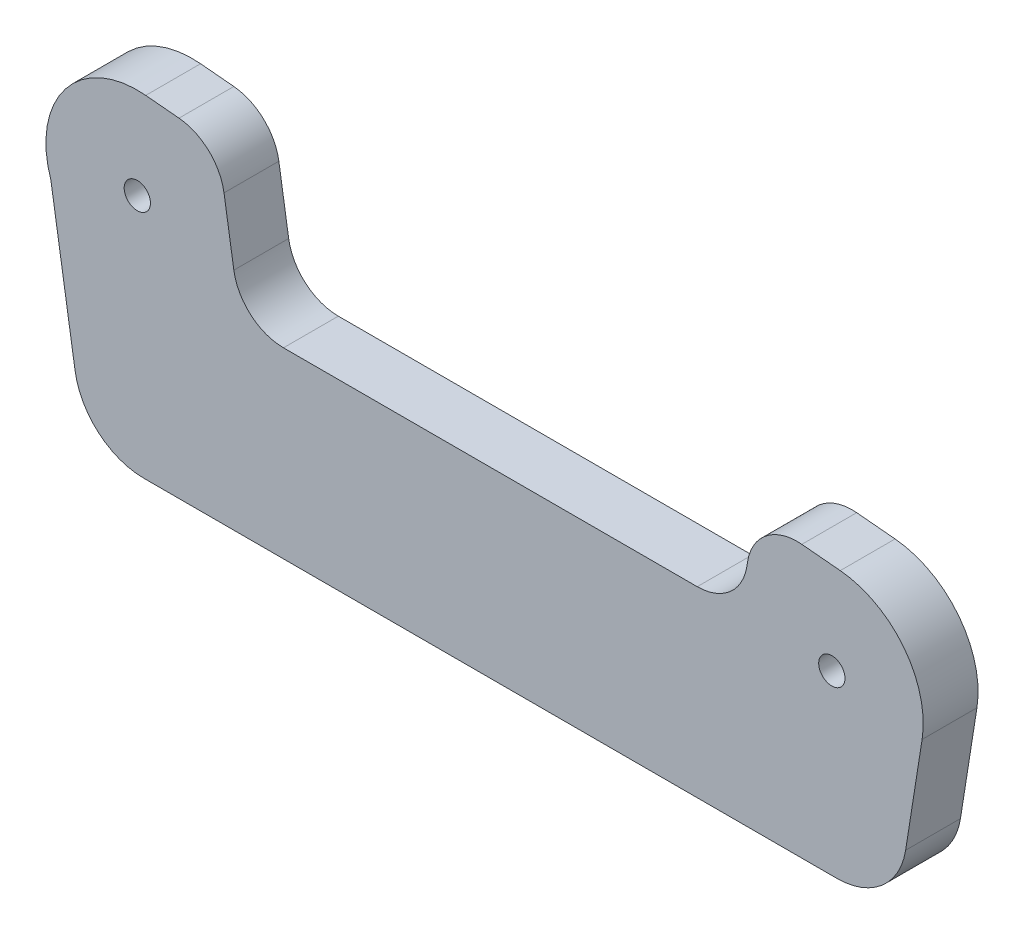
SolidWorks part; units mm, degrees
ref_plane "Front Plane" through (0, 0, 0) normal (0, 0, 1) x (1, 0, 0)
ref_plane "Top Plane" through (0, 0, 0) normal (0, 1, 0) x (1, 0, 0)
ref_plane "Right Plane" through (0, 0, 0) normal (1, 0, 0) x (0, 0, -1)
sketch "Sketch1" plane through (0, 0, 0) normal (0, 0, 1) x (1, 0, 0)
  line L0 (0, 0) -> (69.85, 0) construction
  line L1 (34.925, 0) -> (34.925, 19.3904) construction
  line L2 (-3.067, 19.3904) -> (72.917, 19.3904) construction
  line L3 (0, 0) -> (-3.067, 19.3904) construction
  line L4 (72.917, 19.3904) -> (69.85, 0) construction
  line L5 (-3.067, 19.3904) -> (-3.067, 26.4247) construction
  line L6 (72.917, 19.3904) -> (-3.067, 26.4247) construction
  line L7 (-8.8588, 0) -> (79.9743, 0)
  line L8 (-12.5245, 23.1759) -> (-8.8588, 0)
  line L11 (82.7942, 17.8281) -> (79.9743, 0)
  line L13 (-2.1452, 36.3821) -> (73.8388, 29.3478)
  circle A1 centre (-3.067, 26.4247) radius 1.4375
  circle A2 centre (72.917, 19.3904) radius 1.4375
  arc A6 (82.7942, 17.8281) -> (73.8388, 29.3478) centre (72.917, 19.3904) ccw
  arc A7 (3.7074, 19.0689) -> (4.0399, 19.3896) centre (-3.067, 26.4247) ccw
  circle A8 centre (-3.067, 26.4247) radius 10
  point P7 (34.925, 19.3904)
  dimension "D5" = 20
  dimension "D6" = 10
  dimension "D7" = 2.875
  dimension "D1" = 69.85
  dimension "D2" = 19.3904
  dimension "D3" = 75.984
  dimension "D4" = 7.0343
  dimension "D9" = 0
  dimension "D10" = 8.75
  dimension "D13" = 10
  dimension "D15" = 10
extrude "Boss-Extrude1" add sketch "Sketch1" along normal blind 6 contours A8 L8 L7 L11 A6 L13 A7 A2 | A8 A7 A1
fillet "Fillet3" radius 7.62 2 edges at (79.9743, 0, 3) (-8.8588, 0, 3)
sketch "Sketch2" plane through (0, 0, 6) normal (0, 0, 1) x (1, 0, 0)
  line L0 (-2.1452, 36.3821) -> (73.8388, 29.3478) construction
  ellipse E0 centre (35.8468, 32.865) end of major axis (73.8388, 29.3478) minor radius 6.35
  dimension "D1" = 12.7
extrude "Cut-Extrude1" [suppressed] cut sketch "Sketch2" against normal through all
fillet "Fillet4" [suppressed] radius 6.35
sketch "Sketch3" plane through (0, 0, 6) normal (0, 0, 1) x (1, 0, 0)
  line L6 (5.7508, 35.6511) -> (8.2264, 20)
  line L7 (8.2264, 20) -> (62.8891, 20)
  line L8 (62.8891, 20) -> (64.5044, 30.2119)
  line L9 (64.5044, 30.2119) -> (5.7508, 35.6511)
  line L10 (-12.5245, 23.1759) -> (-9.8758, 6.4295) construction
  line L11 (82.7942, 17.8281) -> (80.9913, 6.4295) construction
  line L12 (-2.1452, 36.3821) -> (73.8388, 29.3478) construction
  line L13 (-2.3493, 0) -> (73.4649, 0) construction
  dimension "D1" = 20
  dimension "D2" = 20
  dimension "D3" = 20
extrude "Cut-Extrude2" cut sketch "Sketch3" against normal through all
fillet "Fillet5" radius 5.5 4 edges at (62.8891, 20, 3) (64.5044, 30.2119, 3) (8.2264, 20, 3) (5.7508, 35.6511, 3)
